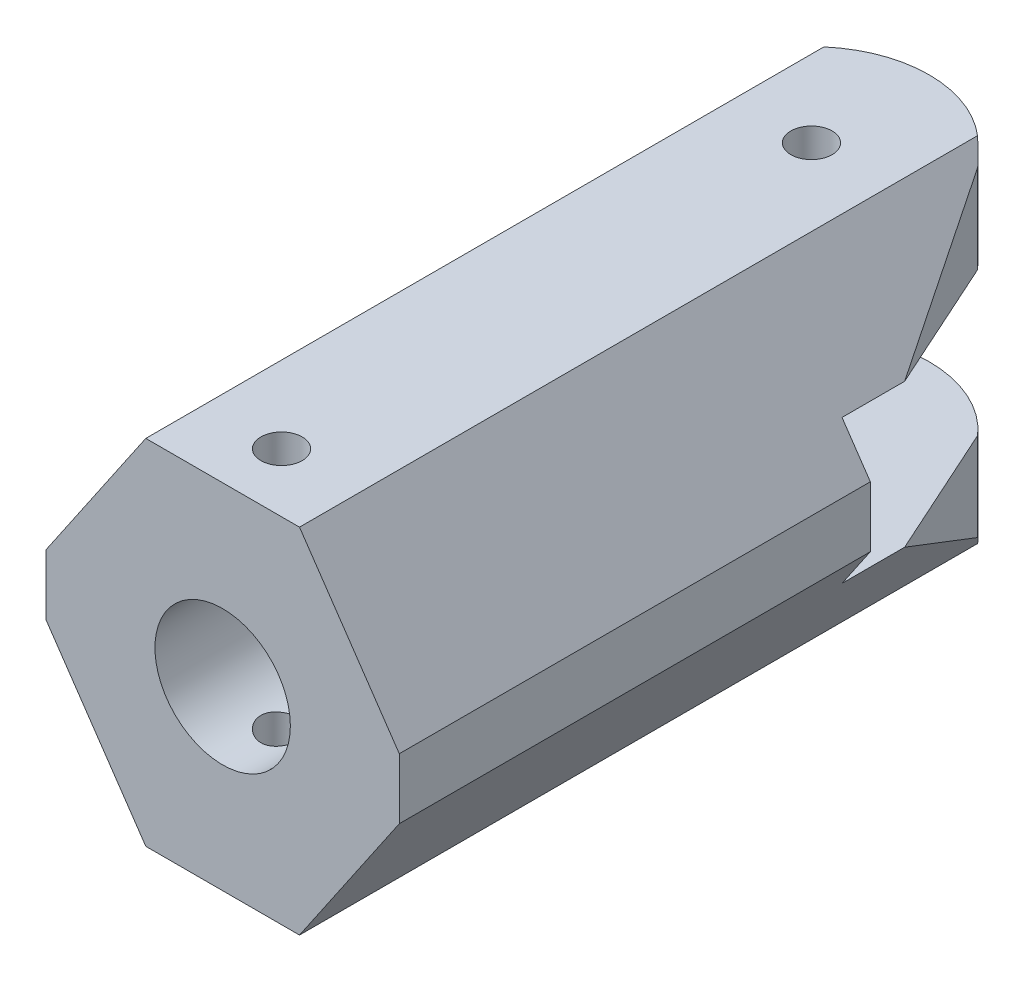
SolidWorks part; units mm, degrees
ref_plane "Front Plane" through (0, 0, 0) normal (0, 0, 1) x (1, 0, 0)
ref_plane "Top Plane" through (0, 0, 0) normal (0, 1, 0) x (1, 0, 0)
ref_plane "Right Plane" through (0, 0, 0) normal (1, 0, 0) x (0, 0, -1)
sketch "Sketch3" plane through (0, 0, 0) normal (0, 0, 1) x (1, 0, 0)
  line L1 (0, 0) -> (30, 0)
  line L2 (0, 0) -> (0, 30)
  line L3 (0, 30) -> (30, 30)
  line L4 (30, 0) -> (30, 30)
  dimension "D1" = 30
  dimension "D2" = 30
extrude "Boss-Extrude1" add sketch "Sketch3" along normal blind 40
sketch "Sketch4" plane through (0, 0, 40) normal (0, 0, 1) x (1, 0, 0)
  line L0 (0, 30) -> (30, 0)
  circle A0 centre (15, 15) radius 5.75
  dimension "D1" = 11.5
extrude "Cut-Extrude1" cut sketch "Sketch4" against normal blind 10 contours L0 A0 | L0 A0
sketch "Sketch5" plane through (0, 0, 0) normal (0, -1, 0) x (1, 0, 0)
  line L0 (15, 40) -> (15, 38.1004)
  line L1 (0, 40) -> (30, 40) construction
  line L2 (15, 36.75) -> (15, 35)
  circle A1 centre (15, 35) radius 1.75
  circle A2 centre (15, 35) radius 3.58
  dimension "D3" = 3.5
  dimension "D1" = 5
extrude "Cut-Extrude2" cut sketch "Sketch5" against normal blind 5
ref_plane "Plane1" through (0, 15, 0) normal (0, -1, 0) x (-1, 0, 0)
sketch "Sketch8" plane through (0, 0, 0) normal (0, 0, -1) x (-1, 0, 0)
  line L0 (-30, 17.573) -> (-21.5266, 30)
  line L1 (-30, 0) -> (-30, 30) construction
  line L2 (-30, 30) -> (0, 30) construction
extrude "Cut-Extrude4" cut sketch "Sketch8" against normal blind 40 and the other way through all
ref_plane "Plane2" through (15, 0, 0) normal (-1, 0, 0) x (0, 0, 1)
mirror "Mirror4" about plane through (15, 0, 0) normal (-1, 0, 0) of "Cut-Extrude4"
mirror "Mirror5" about plane through (0, 15, 0) normal (0, -1, 0) of "Mirror4", "Cut-Extrude4"
sketch "Sketch9" plane through (0, 0, 0) normal (0, 1, 0) x (1, 0, 0)
  line L0 (15, 2.8303) -> (15, -2.8303) construction
  line L1 (21.5266, 0) -> (8.4734, 0) construction
  line L2 (0, 0) -> (5.7692, 13.8462)
  line L3 (30, 0) -> (22.4742, 16.6435)
  line L4 (0, 0) -> (30, 0)
  arc A0 (24.9248, 11.2239) -> (5.7692, 13.8462) centre (15, 10) ccw
  circle A1 centre (15, 10) radius 1.75
  dimension "D1" = 20
  dimension "D2" = 3.5
extrude "Boss-Extrude2" add sketch "Sketch9" along normal blind 30 contours L3 A0 L2 L4 A1
sketch "Sketch10" plane through (0, 0, 0) normal (0, 0, 1) x (1, 0, 0)
  line L0 (0, 17.573) -> (8.4734, 30)
  line L1 (8.4734, 30) -> (0, 30)
  line L2 (0, 30) -> (0, 17.573)
  line L3 (8.4734, 0) -> (0, 0)
  line L4 (0, 0) -> (0, 12.427)
  line L5 (0, 12.427) -> (8.4734, 0)
  line L6 (21.5266, 0) -> (30, 12.427)
  line L7 (30, 12.427) -> (30, 0)
  line L8 (30, 0) -> (21.5266, 0)
  line L9 (30, 17.573) -> (21.5266, 30)
  line L10 (21.5266, 30) -> (30, 30)
  line L11 (30, 30) -> (30, 17.573)
extrude "Cut-Extrude5" cut sketch "Sketch10" against normal blind 30
sketch "Sketch11" plane through (30, 0, 0) normal (1, 0, 0) x (0, 0, -1)
  line L8 (-40, 30) -> (-40, 0)
  line L10 (20, 0) -> (20, 30) construction
  line L11 (0, 21.1) -> (20, 21.1)
  line L12 (0, 21.1) -> (0, 8.9)
  line L13 (0, 8.9) -> (20, 8.9)
  line L14 (20, 21.1) -> (20, 8.9)
  line L15 (17.5765, 30) -> (-40, 30) construction
  dimension "D1" = 0
  dimension "D2" = 8.9
  dimension "D3" = 12.2
  dimension "D4" = 20
extrude "Cut-Extrude6" cut sketch "Sketch11" against normal mid plane 89 contours L14 L11 L12 L13
sketch "Sketch15" plane through (0, 5, 0) normal (0, -1, 0) x (1, 0, 0)
  circle A0 centre (15, 35) radius 1.75
  dimension "D1" = 3.5
extrude "Cut-Extrude8" cut sketch "Sketch15" against normal blind 25
